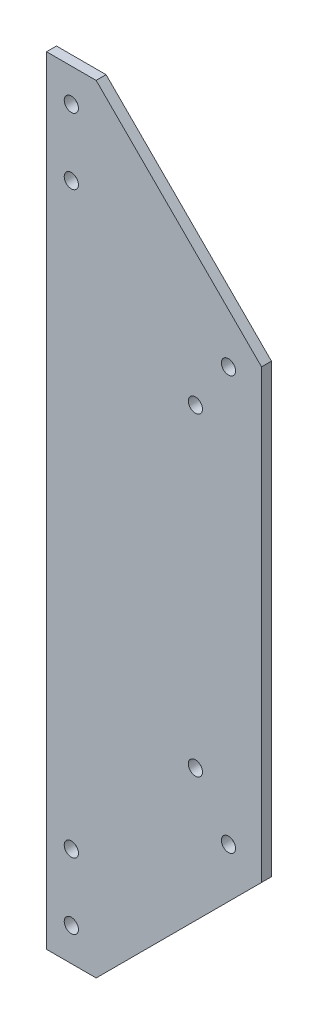
SolidWorks part; units mm, degrees
material "Thornel Mat VMA"
ref_plane "前视基准面" through (0, 0, 0) normal (0, 0, 1) x (1, 0, 0)
ref_plane "上视基准面" through (0, 0, 0) normal (0, 1, 0) x (1, 0, 0)
ref_plane "右视基准面" through (0, 0, 0) normal (1, 0, 0) x (0, 0, -1)
sketch "Sketch1" plane through (0, 0, 0) normal (0, 0, 1) x (1, 0, 0)
  line L0 (-352.3251, 117.5) -> (-352.3251, -117.5)
  line L2 (-352.3251, -117.5) -> (-337.3251, -117.5)
  line L4 (-337.3251, -117.5) -> (-287.3251, -67.5)
  line L5 (-287.3251, -67.5) -> (-287.3251, 67.5)
  line L6 (-287.3251, 67.5) -> (-337.3251, 117.5)
  line L7 (-337.3251, 117.5) -> (-352.3251, 117.5)
  line L8 (-352.3251, 0) -> (-222.9768, 0) construction
  line L10 (327.7002, 47.5) -> (-400.1666, 47.5) construction
  dimension "D1" = 20
extrude "Boss-Extrude1" add sketch "Sketch1" along normal blind 3
sketch "Sketch2" plane through (0, 0, 0) normal (0, 0, -1) x (-1, 0, 0)
  line L0 (344.8251, 117.5) -> (344.8251, -117.5) construction
  line L1 (337.3251, 117.5) -> (352.3251, 117.5) construction
  line L2 (352.3251, -117.5) -> (337.3251, -117.5) construction
  line L3 (352.3251, 0) -> (287.3251, 0) construction
  line L4 (352.3251, 117.5) -> (352.3251, -117.5) construction
  line L5 (287.3251, -67.5) -> (287.3251, 67.5) construction
  line L6 (297.3251, 62.5) -> (297.3251, -57.9654) construction
  circle A0 centre (344.8251, 107.5) radius 2.15
  circle A1 centre (344.8251, 87.5) radius 2.15
  circle A2 centre (344.8251, -87.5) radius 2.15
  circle A3 centre (344.8251, -107.5) radius 2.15
  circle A4 centre (297.3251, 62.5) radius 2.15
  circle A5 centre (307.3251, 47.5) radius 2.15
  circle A6 centre (307.3251, -47.5) radius 2.15
  circle A7 centre (297.3251, -62.5) radius 2.15
  dimension "D1" = 4.3
  dimension "D2" = 10
  dimension "D3" = 20
  dimension "D5" = 5
  dimension "D6" = 20
  dimension "D7" = 15
  dimension "D4" = 10
extrude "Cut-Extrude1" cut sketch "Sketch2" against normal blind 3
